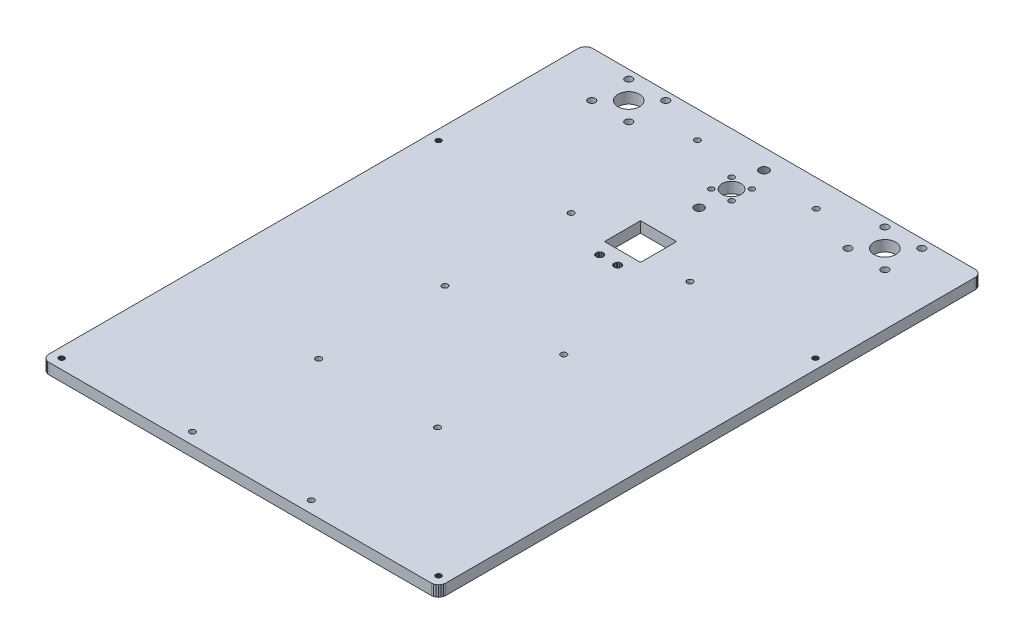
SolidWorks part; units mm, degrees
ref_plane "Alzado" through (0, 0, 0) normal (0, 0, 1) x (1, 0, 0)
ref_plane "Planta" through (0, 0, 0) normal (0, 1, 0) x (1, 0, 0)
ref_plane "Vista lateral" through (0, 0, 0) normal (1, 0, 0) x (0, 0, -1)
sketch "Croquis1" plane through (0, 0, 0) normal (0, 1, 0) x (1, 0, 0)
  line L0 (-2.4786, 139.4098) -> (-2.5, 139.7361)
  line L1 (-2.4148, 139.0891) -> (-2.4786, 139.4098)
  line L2 (-2.3097, 138.7794) -> (-2.4148, 139.0891)
  line L3 (-2.1651, 138.4861) -> (-2.3097, 138.7794)
  line L4 (-1.9834, 138.2142) -> (-2.1651, 138.4861)
  line L5 (-1.7678, 137.9684) -> (-1.9834, 138.2142)
  line L6 (-1.5219, 137.7528) -> (-1.7678, 137.9684)
  line L7 (-1.25, 137.5711) -> (-1.5219, 137.7528)
  line L8 (-0.9567, 137.4264) -> (-1.25, 137.5711)
  line L9 (-0.647, 137.3213) -> (-0.9567, 137.4264)
  line L10 (-0.3263, 137.2575) -> (-0.647, 137.3213)
  line L11 (0, 137.2361) -> (-0.3263, 137.2575)
  line L12 (0.3263, 137.2575) -> (0, 137.2361)
  line L13 (0.647, 137.3213) -> (0.3263, 137.2575)
  line L14 (0.9567, 137.4264) -> (0.647, 137.3213)
  line L15 (1.25, 137.5711) -> (0.9567, 137.4264)
  line L16 (1.5219, 137.7528) -> (1.25, 137.5711)
  line L17 (1.7678, 137.9684) -> (1.5219, 137.7528)
  line L18 (1.9834, 138.2142) -> (1.7678, 137.9684)
  line L19 (2.1651, 138.4861) -> (1.9834, 138.2142)
  line L20 (2.3097, 138.7794) -> (2.1651, 138.4861)
  line L21 (2.4148, 139.0891) -> (2.3097, 138.7794)
  line L22 (2.4786, 139.4098) -> (2.4148, 139.0891)
  line L23 (2.5, 139.7361) -> (2.4786, 139.4098)
  line L24 (-2.4148, 103.0891) -> (-2.4786, 103.4098)
  line L25 (-2.3097, 102.7794) -> (-2.4148, 103.0891)
  line L26 (-2.1651, 102.4861) -> (-2.3097, 102.7794)
  line L27 (-9, 81.2639) -> (9, 81.2639)
  line L28 (-2.4786, 103.4098) -> (-2.5, 103.7361)
  line L29 (-1.9834, 102.2142) -> (-2.1651, 102.4861)
  line L30 (-1.7678, 101.9684) -> (-1.9834, 102.2142)
  line L31 (-1.5219, 101.7528) -> (-1.7678, 101.9684)
  line L32 (-1.25, 101.5711) -> (-1.5219, 101.7528)
  line L33 (-0.9567, 101.4264) -> (-1.25, 101.5711)
  line L34 (-0.647, 101.3213) -> (-0.9567, 101.4264)
  line L35 (-0.3263, 101.2575) -> (-0.647, 101.3213)
  line L36 (0, 101.2361) -> (-0.3263, 101.2575)
  line L37 (0.3263, 101.2575) -> (0, 101.2361)
  line L38 (0.647, 101.3213) -> (0.3263, 101.2575)
  line L39 (0.9567, 101.4264) -> (0.647, 101.3213)
  line L40 (1.25, 101.5711) -> (0.9567, 101.4264)
  line L41 (1.5219, 101.7528) -> (1.25, 101.5711)
  line L42 (1.7678, 101.9684) -> (1.5219, 101.7528)
  line L43 (1.9834, 102.2142) -> (1.7678, 101.9684)
  line L44 (2.1651, 102.4861) -> (1.9834, 102.2142)
  line L45 (2.3097, 102.7794) -> (2.1651, 102.4861)
  line L46 (2.4148, 103.0891) -> (2.3097, 102.7794)
  line L47 (2.4786, 103.4098) -> (2.4148, 103.0891)
  line L48 (2.5, 103.7361) -> (2.4786, 103.4098)
  line L49 (-58.747, 116.0793) -> (-58.747, -150.7361) construction
  line L50 (3.0681, 53.0893) -> (3, 53.6069)
  line L51 (3.2679, 52.6069) -> (3.0681, 53.0893)
  line L52 (3.5858, 52.1927) -> (3.2679, 52.6069)
  line L53 (4, 51.8749) -> (3.5858, 52.1927)
  line L54 (4.4824, 51.6751) -> (4, 51.8749)
  line L55 (5, 51.6069) -> (4.4824, 51.6751)
  line L56 (5.5176, 51.6751) -> (5, 51.6069)
  line L57 (58.747, 145.9892) -> (58.747, -150.7361) construction
  line L58 (6, 51.8749) -> (5.5176, 51.6751)
  line L59 (6.4142, 52.1927) -> (6, 51.8749)
  line L60 (6.7321, 52.6069) -> (6.4142, 52.1927)
  line L61 (6.9319, 53.0893) -> (6.7321, 52.6069)
  line L62 (7, 53.6069) -> (6.9319, 53.0893)
  line L63 (-105.9489, -145.6244) -> (-106, -145.2361)
  line L64 (-105.799, -145.9861) -> (-105.9489, -145.6244)
  line L65 (-105.5607, -146.2968) -> (-105.799, -145.9861)
  line L66 (-105.25, -146.5352) -> (-105.5607, -146.2968)
  line L67 (-104.8882, -146.685) -> (-105.25, -146.5352)
  line L68 (-104.5, -146.7361) -> (-104.8882, -146.685)
  line L69 (-106, -150.7361) -> (106, -150.7361)
  line L70 (-104.1118, -146.685) -> (-104.5, -146.7361)
  line L71 (-103.75, -146.5352) -> (-104.1118, -146.685)
  line L72 (-103.4393, -146.2968) -> (-103.75, -146.5352)
  line L73 (-103.201, -145.9861) -> (-103.4393, -146.2968)
  line L74 (-103.0511, -145.6244) -> (-103.201, -145.9861)
  line L75 (-103, -145.2361) -> (-103.0511, -145.6244)
  line L76 (0, 197.6907) -> (0, 121.7361) construction
  line L77 (60.747, 148.0892) -> (60.747, 143.8892) construction
  line L78 (-71, 135.7361) -> (-8.3, 135.7361) construction
  line L79 (71, 135.7361) -> (71, -150.7361) construction
  line L80 (58.747, 145.9892) -> (58.747, 157.4372) construction
  line L81 (0, 150.7361) -> (-7.1569, 150.7361) construction
  line L82 (-32.9519, 150.7361) -> (-32.9519, -150.7361) construction
  line L83 (-58.747, 150.7361) -> (-7.1569, 150.7361)
  line L84 (32.9519, 150.7361) -> (32.9519, -150.7361) construction
  line L85 (71, 135.7361) -> (8.3, 135.7361) construction
  line L86 (-7.1569, 128.893) -> (-7.1569, 127.393)
  line L87 (-58.747, 150.7361) -> (-106, 150.7361)
  line L98 (0, 121.7361) -> (0, -150.7361) construction
  line L150 (10, 62.2639) -> (10, 61.2639)
  line L151 (103.201, -145.9861) -> (103.0511, -145.6244)
  line L152 (10, 80.2639) -> (10, 62.2639)
  line L189 (103.0511, -145.6244) -> (103, -145.2361)
  line L244 (103.4393, -146.2968) -> (103.201, -145.9861)
  line L245 (103.75, -146.5352) -> (103.4393, -146.2968)
  line L246 (104.1118, -146.685) -> (103.75, -146.5352)
  line L247 (104.5, -146.7361) -> (104.1118, -146.685)
  line L248 (104.8882, -146.685) -> (104.5, -146.7361)
  line L249 (105.25, -146.5352) -> (104.8882, -146.685)
  line L250 (105.5607, -146.2968) -> (105.25, -146.5352)
  line L251 (105.799, -145.9861) -> (105.5607, -146.2968)
  line L252 (105.9489, -145.6244) -> (105.799, -145.9861)
  line L253 (106, -145.2361) -> (105.9489, -145.6244)
  line L254 (106, -150.7361) -> (107.0353, -150.5998)
  line L255 (107.0353, 150.5998) -> (106, 150.7361)
  line L256 (107.0353, -150.5998) -> (108, -150.2002)
  line L257 (108, 150.2002) -> (107.0353, 150.5998)
  line L258 (108, -150.2002) -> (108.8284, -149.5646)
  line L259 (108.8284, 149.5646) -> (108, 150.2002)
  line L260 (108.8284, -149.5646) -> (109.4641, -148.7361)
  line L261 (109.4641, 148.7361) -> (108.8284, 149.5646)
  line L262 (109.4641, -148.7361) -> (109.8637, -147.7714)
  line L263 (109.8637, 147.7714) -> (109.4641, 148.7361)
  line L264 (109.8637, -147.7714) -> (110, -146.7361)
  line L265 (110, -146.7361) -> (110, 146.7361)
  line L266 (110, 146.7361) -> (109.8637, 147.7714)
  line L267 (-110, 146.7361) -> (-110, -146.7361)
  line L268 (-110, -146.7361) -> (-109.8637, -147.7714)
  line L269 (-109.8637, 147.7714) -> (-110, 146.7361)
  line L270 (-109.8637, -147.7714) -> (-109.4641, -148.7361)
  line L271 (-109.4641, 148.7361) -> (-109.8637, 147.7714)
  line L272 (-109.4641, -148.7361) -> (-108.8284, -149.5646)
  line L273 (-108.8284, 149.5646) -> (-109.4641, 148.7361)
  line L274 (-108.8284, -149.5646) -> (-108, -150.2002)
  line L275 (-108, 150.2002) -> (-108.8284, 149.5646)
  line L276 (-108, -150.2002) -> (-107.0353, -150.5998)
  line L277 (-107.0353, 150.5998) -> (-108, 150.2002)
  line L278 (-107.0353, -150.5998) -> (-106, -150.7361)
  line L279 (-106, 150.7361) -> (-107.0353, 150.5998)
  line L280 (-106, 63.7639) -> (-105.9489, 64.1521)
  line L291 (106, 150.7361) -> (-7.1569, 150.7361)
  line L292 (-105.9489, 64.1521) -> (-105.799, 64.5139)
  line L293 (-105.799, 64.5139) -> (-105.5607, 64.8245)
  line L294 (-105.5607, 64.8245) -> (-105.25, 65.0629)
  line L295 (-105.25, 65.0629) -> (-104.8882, 65.2128)
  line L296 (-104.8882, 65.2128) -> (-104.5, 65.2639)
  line L297 (-104.5, 65.2639) -> (-104.1118, 65.2128)
  line L298 (-104.1118, 65.2128) -> (-103.75, 65.0629)
  line L299 (-103.75, 65.0629) -> (-103.4393, 64.8245)
  line L300 (-103.4393, 64.8245) -> (-103.201, 64.5139)
  line L301 (-103.201, 64.5139) -> (-103.0511, 64.1521)
  line L302 (-103.0511, 64.1521) -> (-103, 63.7639)
  line L358 (-0.647, 142.151) -> (-0.3263, 142.2147)
  line L359 (-0.9567, 142.0458) -> (-0.647, 142.151)
  line L360 (-1.25, 141.9012) -> (-0.9567, 142.0458)
  line L361 (-1.5219, 141.7195) -> (-1.25, 141.9012)
  line L362 (-1.7678, 141.5039) -> (-1.5219, 141.7195)
  line L363 (-1.9834, 141.258) -> (-1.7678, 141.5039)
  line L364 (-2.1651, 140.9861) -> (-1.9834, 141.258)
  line L365 (-2.3097, 140.6928) -> (-2.1651, 140.9861)
  line L366 (-2.4148, 140.3832) -> (-2.3097, 140.6928)
  line L367 (-2.4786, 140.0625) -> (-2.4148, 140.3832)
  line L368 (-10, 61.2639) -> (-10, 62.2639)
  line L369 (-10, 81.2639) -> (-9, 81.2639)
  line L370 (-2.5, 139.7361) -> (-2.4786, 140.0625)
  line L371 (-0.3263, 142.2147) -> (0, 142.2361)
  line L372 (0, 142.2361) -> (0.3263, 142.2147)
  line L373 (0.3263, 142.2147) -> (0.647, 142.151)
  line L374 (0.647, 142.151) -> (0.9567, 142.0458)
  line L375 (0.9567, 142.0458) -> (1.25, 141.9012)
  line L376 (1.25, 141.9012) -> (1.5219, 141.7195)
  line L377 (1.5219, 141.7195) -> (1.7678, 141.5039)
  line L378 (1.7678, 141.5039) -> (1.9834, 141.258)
  line L379 (1.9834, 141.258) -> (2.1651, 140.9861)
  line L380 (2.1651, 140.9861) -> (2.3097, 140.6928)
  line L381 (2.3097, 140.6928) -> (2.4148, 140.3832)
  line L382 (2.4148, 140.3832) -> (2.4786, 140.0625)
  line L383 (2.4786, 140.0625) -> (2.5, 139.7361)
  line L386 (9, 81.2639) -> (10, 81.2639)
  line L387 (10, 81.2639) -> (10, 80.2639)
  line L476 (103, 63.7639) -> (103.0511, 64.1521)
  line L477 (103.0511, 64.1521) -> (103.201, 64.5139)
  line L478 (103.201, 64.5139) -> (103.4393, 64.8245)
  line L479 (103.4393, 64.8245) -> (103.75, 65.0629)
  line L480 (103.75, 65.0629) -> (104.1118, 65.2128)
  line L481 (104.1118, 65.2128) -> (104.5, 65.2639)
  line L482 (104.5, 65.2639) -> (104.8882, 65.2128)
  line L483 (104.8882, 65.2128) -> (105.25, 65.0629)
  line L484 (105.25, 65.0629) -> (105.5607, 64.8245)
  line L485 (105.5607, 64.8245) -> (105.799, 64.5139)
  line L486 (105.799, 64.5139) -> (105.9489, 64.1521)
  line L487 (105.9489, 64.1521) -> (106, 63.7639)
  line L488 (103, -145.2361) -> (103.0511, -144.8479)
  line L489 (103.0511, 63.3756) -> (103, 63.7639)
  line L490 (103.0511, -144.8479) -> (103.201, -144.4861)
  line L491 (103.201, 63.0139) -> (103.0511, 63.3756)
  line L492 (103.201, -144.4861) -> (103.4393, -144.1755)
  line L493 (103.4393, 62.7032) -> (103.201, 63.0139)
  line L494 (103.4393, -144.1755) -> (103.75, -143.9371)
  line L495 (103.75, 62.4648) -> (103.4393, 62.7032)
  line L496 (103.75, -143.9371) -> (104.1118, -143.7872)
  line L497 (104.1118, 62.315) -> (103.75, 62.4648)
  line L498 (104.1118, -143.7872) -> (104.5, -143.7361)
  line L499 (104.5, 62.2639) -> (104.1118, 62.315)
  line L500 (104.5, -143.7361) -> (104.8882, -143.7872)
  line L501 (104.8882, 62.315) -> (104.5, 62.2639)
  line L502 (104.8882, -143.7872) -> (105.25, -143.9371)
  line L503 (105.25, 62.4648) -> (104.8882, 62.315)
  line L504 (105.25, -143.9371) -> (105.5607, -144.1755)
  line L505 (105.5607, 62.7032) -> (105.25, 62.4648)
  line L506 (105.5607, -144.1755) -> (105.799, -144.4861)
  line L507 (105.799, 63.0139) -> (105.5607, 62.7032)
  line L508 (105.799, -144.4861) -> (105.9489, -144.8479)
  line L509 (105.9489, 63.3756) -> (105.799, 63.0139)
  line L510 (105.9489, -144.8479) -> (106, -145.2361)
  line L511 (106, 63.7639) -> (105.9489, 63.3756)
  line L622 (-9, 61.2639) -> (-10, 61.2639)
  line L624 (-7, 53.6069) -> (-6.9319, 54.1246)
  line L625 (-6.9319, 54.1246) -> (-6.7321, 54.6069)
  line L626 (-6.7321, 54.6069) -> (-6.4142, 55.0211)
  line L627 (-6.4142, 55.0211) -> (-6, 55.339)
  line L628 (-6, 55.339) -> (-5.5176, 55.5388)
  line L629 (9, 61.2639) -> (-9, 61.2639)
  line L631 (-5.5176, 55.5388) -> (-5, 55.6069)
  line L632 (-5, 55.6069) -> (-4.4824, 55.5388)
  line L633 (-4.4824, 55.5388) -> (-4, 55.339)
  line L634 (-4, 55.339) -> (-3.5858, 55.0211)
  line L635 (-3.5858, 55.0211) -> (-3.2679, 54.6069)
  line L636 (-3.2679, 54.6069) -> (-3.0681, 54.1246)
  line L637 (-3.0681, 54.1246) -> (-3, 53.6069)
  line L638 (3.2679, 54.6069) -> (3.5858, 55.0211)
  line L639 (3.0681, 54.1246) -> (3.2679, 54.6069)
  line L640 (3, 53.6069) -> (3.0681, 54.1246)
  line L643 (3.5858, 55.0211) -> (4, 55.339)
  line L644 (4, 55.339) -> (4.4824, 55.5388)
  line L645 (4.4824, 55.5388) -> (5, 55.6069)
  line L646 (5, 55.6069) -> (5.5176, 55.5388)
  line L647 (5.5176, 55.5388) -> (6, 55.339)
  line L648 (6, 55.339) -> (6.4142, 55.0211)
  line L649 (6.4142, 55.0211) -> (6.7321, 54.6069)
  line L650 (6.7321, 54.6069) -> (6.9319, 54.1246)
  line L651 (6.9319, 54.1246) -> (7, 53.6069)
  line L654 (10, 61.2639) -> (9, 61.2639)
  line L656 (-2.5, 103.7361) -> (-2.4786, 104.0625)
  line L657 (-2.4786, 104.0625) -> (-2.4148, 104.3832)
  line L658 (-2.4148, 104.3832) -> (-2.3097, 104.6928)
  line L659 (-2.3097, 104.6928) -> (-2.1651, 104.9861)
  line L660 (-2.1651, 104.9861) -> (-1.9834, 105.258)
  line L661 (-1.9834, 105.258) -> (-1.7678, 105.5039)
  line L662 (-1.7678, 105.5039) -> (-1.5219, 105.7195)
  line L663 (-1.5219, 105.7195) -> (-1.25, 105.9012)
  line L664 (-1.25, 105.9012) -> (-0.9567, 106.0458)
  line L665 (-0.9567, 106.0458) -> (-0.647, 106.151)
  line L666 (-0.647, 106.151) -> (-0.3263, 106.2147)
  line L667 (-0.3263, 106.2147) -> (0, 106.2361)
  line L668 (0, 106.2361) -> (0.3263, 106.2147)
  line L669 (0.3263, 106.2147) -> (0.647, 106.151)
  line L670 (0.647, 106.151) -> (0.9567, 106.0458)
  line L671 (0.9567, 106.0458) -> (1.25, 105.9012)
  line L672 (1.25, 105.9012) -> (1.5219, 105.7195)
  line L673 (1.5219, 105.7195) -> (1.7678, 105.5039)
  line L674 (1.7678, 105.5039) -> (1.9834, 105.258)
  line L675 (1.9834, 105.258) -> (2.1651, 104.9861)
  line L676 (2.1651, 104.9861) -> (2.3097, 104.6928)
  line L677 (2.3097, 104.6928) -> (2.4148, 104.3832)
  line L678 (2.4148, 104.3832) -> (2.4786, 104.0625)
  line L679 (2.4786, 104.0625) -> (2.5, 103.7361)
  line L680 (-10, 80.2639) -> (-10, 81.2639)
  line L681 (-10, 62.2639) -> (-10, 80.2639)
  line L683 (-6.9319, 53.0893) -> (-7, 53.6069)
  line L684 (-6.7321, 52.6069) -> (-6.9319, 53.0893)
  line L685 (-6.4142, 52.1927) -> (-6.7321, 52.6069)
  line L686 (-6, 51.8749) -> (-6.4142, 52.1927)
  line L687 (-5.5176, 51.6751) -> (-6, 51.8749)
  line L688 (-5, 51.6069) -> (-5.5176, 51.6751)
  line L689 (-4.4824, 51.6751) -> (-5, 51.6069)
  line L691 (-4, 51.8749) -> (-4.4824, 51.6751)
  line L692 (-3.5858, 52.1927) -> (-4, 51.8749)
  line L693 (-3.2679, 52.6069) -> (-3.5858, 52.1927)
  line L694 (-3.0681, 53.0893) -> (-3.2679, 52.6069)
  line L695 (-3, 53.6069) -> (-3.0681, 53.0893)
  line L798 (-106, -145.2361) -> (-105.9489, -144.8479)
  line L799 (-105.9489, 63.3756) -> (-106, 63.7639)
  line L800 (-105.9489, -144.8479) -> (-105.799, -144.4861)
  line L801 (-105.799, 63.0139) -> (-105.9489, 63.3756)
  line L802 (-105.799, -144.4861) -> (-105.5607, -144.1755)
  line L803 (-105.5607, 62.7032) -> (-105.799, 63.0139)
  line L804 (-105.5607, -144.1755) -> (-105.25, -143.9371)
  line L805 (-105.25, 62.4648) -> (-105.5607, 62.7032)
  line L806 (-105.25, -143.9371) -> (-104.8882, -143.7872)
  line L807 (-104.8882, 62.315) -> (-105.25, 62.4648)
  line L808 (-104.8882, -143.7872) -> (-104.5, -143.7361)
  line L809 (-104.5, 62.2639) -> (-104.8882, 62.315)
  line L810 (-104.5, -143.7361) -> (-104.1118, -143.7872)
  line L811 (-104.1118, 62.315) -> (-104.5, 62.2639)
  line L812 (-104.1118, -143.7872) -> (-103.75, -143.9371)
  line L813 (-103.75, 62.4648) -> (-104.1118, 62.315)
  line L814 (-103.75, -143.9371) -> (-103.4393, -144.1755)
  line L815 (-103.4393, 62.7032) -> (-103.75, 62.4648)
  line L816 (-103.4393, -144.1755) -> (-103.201, -144.4861)
  line L817 (-103.201, 63.0139) -> (-103.4393, 62.7032)
  line L818 (-103.201, -144.4861) -> (-103.0511, -144.8479)
  line L819 (-103.0511, 63.3756) -> (-103.201, 63.0139)
  line L820 (-103.0511, -144.8479) -> (-103, -145.2361)
  line L821 (-103, 63.7639) -> (-103.0511, 63.3756)
  line L822 (-8.3, 113.4361) -> (8.3, 130.0361) construction
  line L823 (-8.3, 130.0361) -> (8.3, 113.4361) construction
  line L824 (-81.253, 148.0892) -> (-81.253, 143.8892) construction
  circle A0 centre (0, 121.7361) radius 5.25
  circle A1 centre (5.6569, 127.393) radius 1.5
  circle A2 centre (-5.6569, 127.393) radius 1.5
  circle A3 centre (-5.6569, 116.0793) radius 1.5
  circle A4 centre (5.6569, 116.0793) radius 1.5
  circle A5 centre (-81.253, 145.9892) radius 2
  circle A6 centre (-60.747, 145.9892) radius 2
  circle A7 centre (-81.253, 125.4831) radius 2
  circle A8 centre (-60.747, 125.4831) radius 2
  circle A9 centre (-71, 135.7361) radius 6
  circle A10 centre (60.747, 145.9892) radius 2
  circle A11 centre (81.253, 145.9892) radius 2
  circle A12 centre (60.747, 125.4831) radius 2
  circle A13 centre (81.253, 125.4831) radius 2
  circle A14 centre (60.747, 145.9892) radius 2
  circle A15 centre (81.253, 145.9892) radius 2
  circle A16 centre (60.747, 125.4831) radius 2
  circle A17 centre (81.253, 125.4831) radius 2
  circle A18 centre (71, 135.7361) radius 6
  circle A19 centre (-32.9519, 135.7361) radius 1.6
  circle A20 centre (-32.9519, 65.7361) radius 1.6
  circle A21 centre (-32.9519, -4.2639) radius 1.6
  circle A22 centre (-32.9519, -74.2639) radius 1.6
  circle A23 centre (-32.9519, -144.2639) radius 1.6
  circle A24 centre (32.9519, -144.2639) radius 1.6
  circle A25 centre (32.9519, -74.2639) radius 1.6
  circle A26 centre (32.9519, -4.2639) radius 1.6
  circle A27 centre (32.9519, 65.7361) radius 1.6
  circle A28 centre (32.9519, 135.7361) radius 1.6
  point P113 (-71, -145.2361)
  dimension "D2" = 4
  dimension "D3" = 4
  dimension "D4" = 4
  dimension "D5" = 12
  dimension "D6" = 4
  dimension "D7" = 4
  dimension "D8" = 4
  dimension "D9" = 4
  dimension "D10" = 4
  dimension "D11" = 4
  dimension "D12" = 4
  dimension "D13" = 12
  dimension "D14" = 5
  dimension "D1" = 11.3137
extrude "Saliente-Extruir1" add sketch "Croquis1" along normal blind 6
